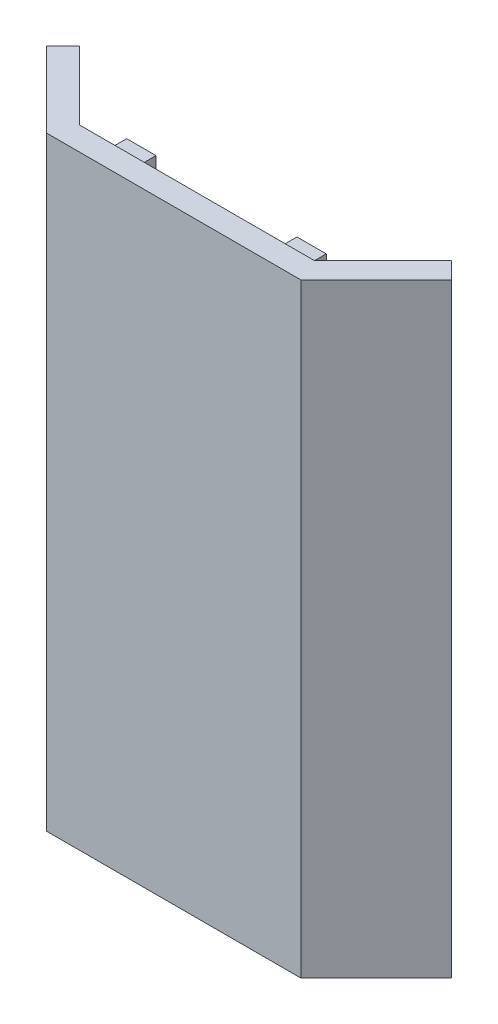
SolidWorks part; units mm, degrees
material "3.0205 (EN-AW 1200)"
ref_plane "Alzado" through (0, 0, 0) normal (0, 0, 1) x (1, 0, 0)
ref_plane "Planta" through (0, 0, 0) normal (0, 1, 0) x (1, 0, 0)
ref_plane "Vista lateral" through (0, 0, 0) normal (1, 0, 0) x (0, 0, -1)
sketch "Croquis1" plane through (0, 0, 0) normal (0, 1, 0) x (1, 0, 0)
  line L0 (-40, 0) -> (40, 0)
  line L1 (40, 0) -> (63.3345, 23.3345)
  line L2 (-40, 0) -> (-63.3345, 23.3345)
  line L3 (-43.3137, -8) -> (-68.9914, 17.6777)
  line L5 (-43.3137, -8) -> (43.3137, -8)
  line L6 (43.3137, -8) -> (68.9914, 17.6777)
  line L7 (-68.9914, 17.6777) -> (-63.3345, 23.3345)
  line L8 (63.3345, 23.3345) -> (68.9914, 17.6777)
  dimension "D1" = 33
  dimension "D2" = 33
  dimension "D3" = 8
  dimension "D4" = 80
  dimension "D5" = 135
  dimension "D6" = 135
extrude "Saliente-Extruir1" add sketch "Croquis1" along normal mid plane 206 contours L5 L6 L8 L1 L0 L2 L7 L3
sketch "Croquis2" plane through (0, 0, 0) normal (0, 0, -1) x (-1, 0, 0)
  line L0 (0, 0) -> (0, 103) construction
  line L1 (40, 103) -> (-40, 103) construction
  line L2 (34, -97) -> (34, -91)
  line L3 (-34, -97) -> (-24, -97)
  line L4 (-34, -97) -> (-34, -91)
  line L5 (-34, -91) -> (-24, -91)
  line L6 (-24, -97) -> (-24, -91)
  line L7 (34, -97) -> (24, -97)
  line L8 (24, -97) -> (24, -91)
  line L9 (34, -91) -> (24, -91)
  line L10 (-40, 103) -> (-40, -103) construction
  line L11 (40, -103) -> (-40, -103) construction
  dimension "D1" = 10
  dimension "D2" = 6
  dimension "D3" = 6
  dimension "D4" = 6
extrude "Saliente-Extruir2" add sketch "Croquis2" along normal blind 10
mirror "Simetría2" about plane through (0, 0, 0) normal (0, 1, 0) of "Saliente-Extruir2"
